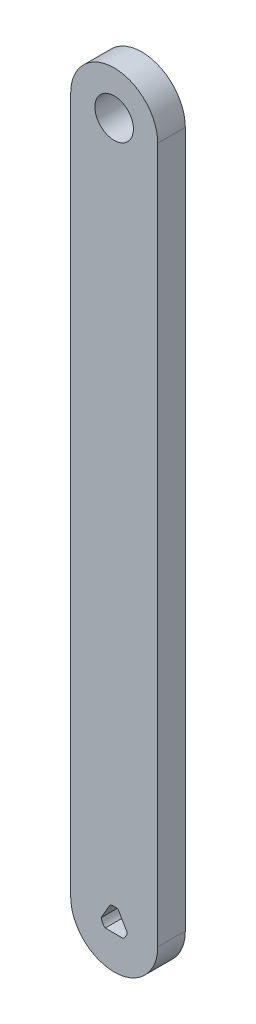
SolidWorks part; units mm, degrees
material "ABS"
ref_plane "Plano frontal" through (0, 0, 0) normal (0, 0, 1) x (1, 0, 0)
ref_plane "Plano superior" through (0, 0, 0) normal (0, 1, 0) x (1, 0, 0)
ref_plane "Plano direito" through (0, 0, 0) normal (1, 0, 0) x (0, 0, -1)
sketch "Esboço1" plane through (0, 0, 0) normal (0, 0, 1) x (1, 0, 0)
  line L0 (0, 0) -> (0, 120) construction
  line L1 (-7.5, 0) -> (-7.5, 120)
  line L2 (7.5, 0) -> (7.5, 120)
  line L3 (2.2468, -0.4916) -> (0.6976, 2.1916)
  line L4 (-0.6976, 2.1916) -> (-2.2468, -0.4916)
  line L5 (1.5492, -1.7) -> (-1.5492, -1.7)
  line L6 (1.4722, 0.85) -> (-1.9919, -1.15) construction
  line L7 (0, -1.7) -> (0, 2.3) construction
  arc A0 (-7.5, 0) -> (7.5, 0) centre (0, 0) ccw
  arc A1 (7.5, 120) -> (-7.5, 120) centre (0, 120) ccw
  arc A2 (1.5492, -1.7) -> (2.2468, -0.4916) centre (0, 0) ccw
  arc A3 (0.6976, 2.1916) -> (-0.6976, 2.1916) centre (0, 0) ccw
  arc A4 (-1.5492, -1.7) -> (-2.2468, -0.4916) centre (0, 0) cw
  circle A5 centre (0, 120) radius 3.325
  point P3 (0, 60)
  dimension "D1" = 2.3
  dimension "D3" = 6.65
  dimension "D2" = 4
  dimension "D4" = 120
  dimension "D5" = 15
extrude "Ressalto-extrusão1" add sketch "Esboço1" along normal blind 4.7625
